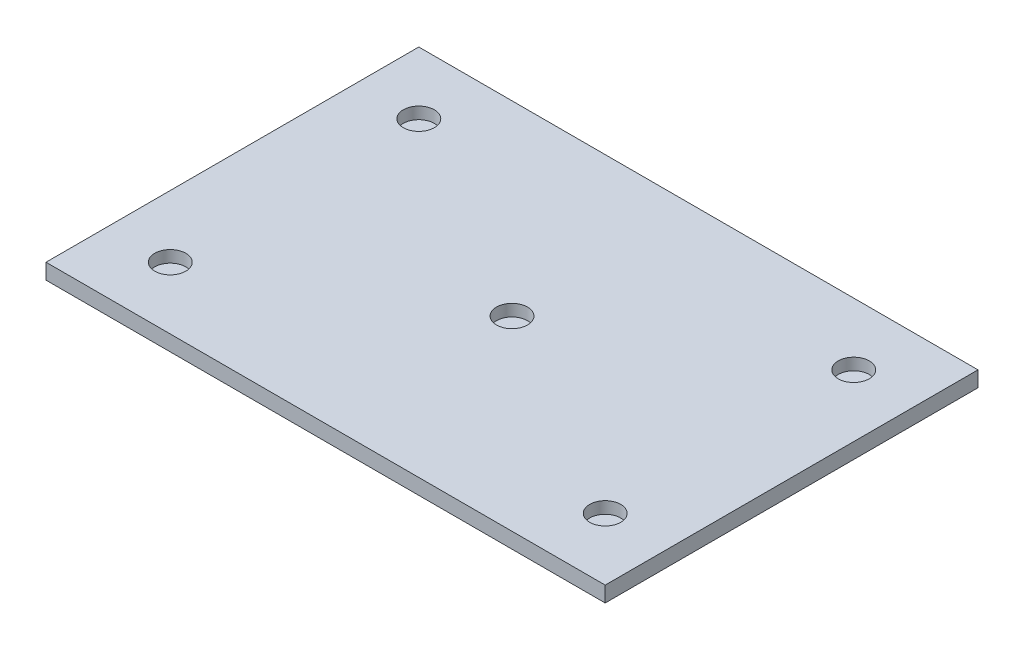
SolidWorks part; units mm, degrees
material "PE High Density Film"
ref_plane "Front Plane" through (0, 0, 0) normal (0, 0, 1) x (1, 0, 0)
ref_plane "Top Plane" through (0, 0, 0) normal (0, 1, 0) x (1, 0, 0)
ref_plane "Right Plane" through (0, 0, 0) normal (1, 0, 0) x (0, 0, -1)
sketch "Sketch1" plane through (0, 0, 0) normal (0, 1, 0) x (1, 0, 0)
  line L1 (-114.3, 76.2) -> (114.3, 76.2)
  line L2 (-114.3, 76.2) -> (-114.3, -76.2)
  line L3 (-114.3, -76.2) -> (114.3, -76.2)
  line L4 (114.3, 76.2) -> (114.3, -76.2)
  line L5 (-114.3, 76.2) -> (114.3, -76.2) construction
  line L6 (-114.3, -76.2) -> (114.3, 76.2) construction
  point P0 (0, 0)
  dimension "D1" = 228.6
  dimension "D2" = 152.4
extrude "Boss-Extrude1" add sketch "Sketch1" along normal blind 6.35
sketch "Sketch2" plane through (0, 6.35, 0) normal (0, 1, 0) x (1, 0, 0)
  line L0 (0, 0) -> (0, 76.2) construction
  line L5 (0, 0) -> (-114.3, 0) construction
  line L6 (-114.3, 76.2) -> (-114.3, -76.2) construction
  line L7 (114.3, 76.2) -> (-114.3, 76.2) construction
  circle A0 centre (-88.9, 50.8) radius 6.35
  circle A1 centre (-88.9, -50.8) radius 6.35
  circle A2 centre (88.9, -50.8) radius 6.35
  circle A3 centre (88.9, 50.8) radius 6.35
  circle A4 centre (0, 0) radius 6.35
  dimension "D3" = 12.7
  dimension "D4" = 12.7
  dimension "D1" = 25.4
  dimension "D2" = 25.4
extrude "Cut-Extrude1" cut sketch "Sketch2" against normal blind 4.826
